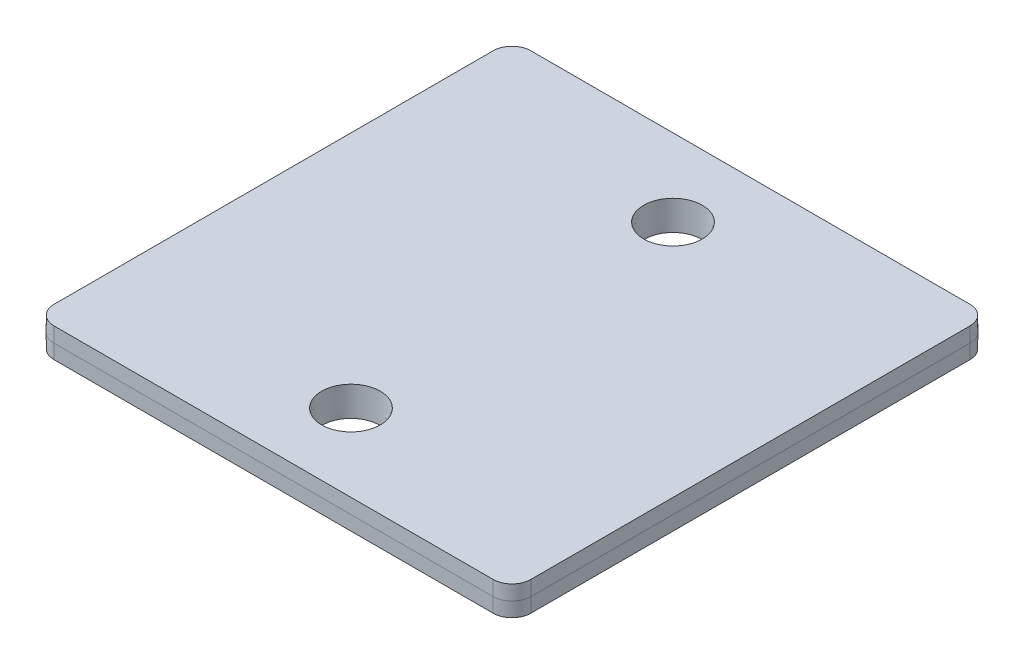
SolidWorks part; units mm, degrees
ref_plane "Front Plane" through (0, 0, 0) normal (0, 0, 1) x (1, 0, 0)
ref_plane "Top Plane" through (0, 0, 0) normal (0, 1, 0) x (1, 0, 0)
ref_plane "Right Plane" through (0, 0, 0) normal (1, 0, 0) x (0, 0, -1)
sketch "Sketch2" plane through (0, 0, 0) normal (0, 1, 0) x (1, 0, 0)
  line L0 (-8.1499, 7.5) -> (-8.1499, -7.5)
  line L1 (-7.5, -8.1499) -> (7.5, -8.1499)
  line L2 (8.1499, -7.5) -> (8.1499, 7.5)
  line L3 (7.5, 8.1499) -> (-7.5, 8.1499)
  arc A0 (-8.1499, -7.5) -> (-7.5, -8.1499) centre (-7.5, -7.5) ccw
  arc A1 (7.5, -8.1499) -> (8.1499, -7.5) centre (7.5, -7.5) ccw
  arc A2 (8.1499, 7.5) -> (7.5, 8.1499) centre (7.5, 7.5) ccw
  arc A3 (-7.5, 8.1499) -> (-8.1499, 7.5) centre (-7.5, 7.5) ccw
  dimension "D1" = 8.1499
  dimension "D2" = 8.1499
  dimension "D3" = 8.1499
  dimension "D4" = 8.1499
extrude "Boss-Extrude1" add sketch "Sketch2" along normal mid plane 1 draft 1
sketch "Sketch3" plane through (0, 0.5, 0) normal (0, 1, 0) x (1, 0, 0)
  line L0 (0, -0.55) -> (0, 0.55) construction
  line L1 (-0.55, 0) -> (0.55, 0) construction
  circle A0 centre (0, 5.5) radius 1
  circle A1 centre (0, -5.5) radius 1
  dimension "D1" = 5.5
  dimension "D2" = 5.5
extrude "Cut-Extrude1" cut sketch "Sketch3" against normal blind 10 draft 1
